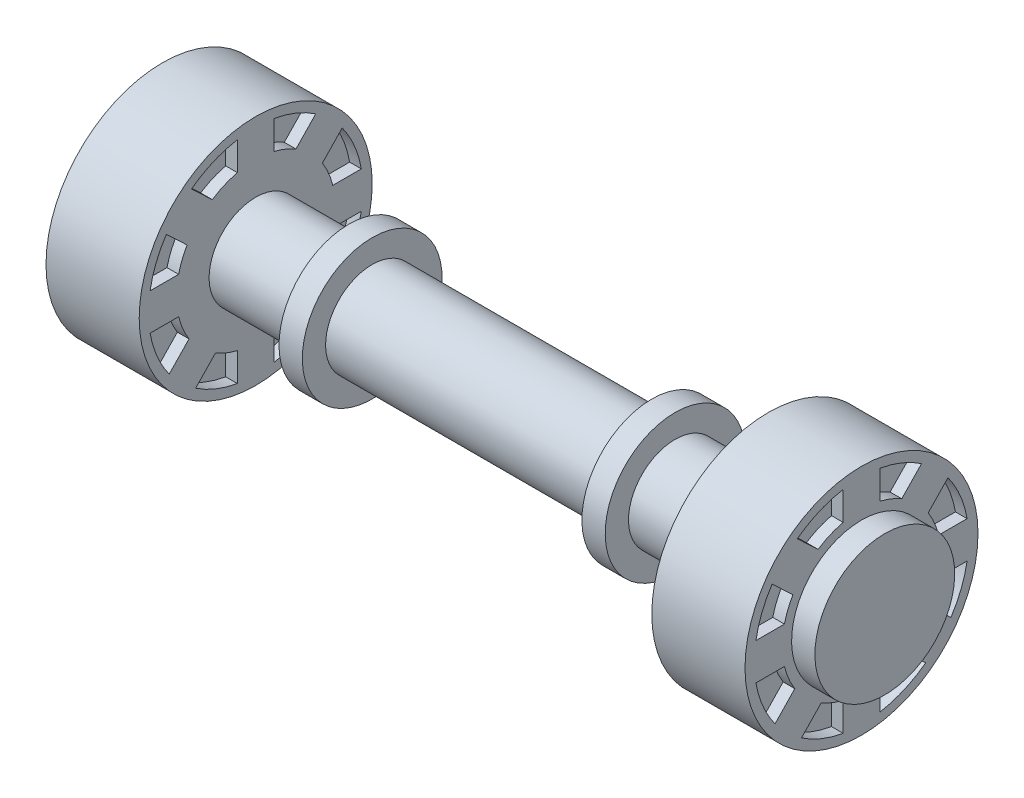
SolidWorks part; units mm, degrees
ref_plane "Front Plane" through (0, 0, 0) normal (0, 0, 1) x (1, 0, 0)
ref_plane "Top Plane" through (0, 0, 0) normal (0, 1, 0) x (1, 0, 0)
ref_plane "Right Plane" through (0, 0, 0) normal (1, 0, 0) x (0, 0, -1)
sketch "Sketch1" plane through (0, 0, 0) normal (0, 0, 1) x (1, 0, 0)
  line L0 (203.2, 0) -> (-203.2, 0)
  line L5 (-139.7, 25.4) -> (-139.7, 63.5)
  line L6 (-139.7, 63.5) -> (-190.5, 63.5)
  line L7 (-139.7, 25.4) -> (-88.9, 25.4)
  line L12 (-88.9, 25.4) -> (-88.9, 38.1)
  line L13 (-88.9, 38.1) -> (-76.2, 38.1)
  line L14 (-76.2, 38.1) -> (-76.2, 25.4)
  line L15 (-76.2, 25.4) -> (76.2, 25.4)
  line L16 (76.2, 25.4) -> (76.2, 38.1)
  line L17 (76.2, 38.1) -> (88.9, 38.1)
  line L18 (88.9, 38.1) -> (88.9, 25.4)
  line L19 (88.9, 25.4) -> (139.7, 25.4)
  line L20 (139.7, 25.4) -> (139.7, 63.5)
  line L21 (139.7, 63.5) -> (190.5, 63.5)
  line L22 (190.5, 63.5) -> (190.5, 38.1)
  line L23 (190.5, 38.1) -> (203.2, 38.1)
  line L24 (203.2, 38.1) -> (203.2, 0)
  line L25 (-190.5, 63.5) -> (-190.5, 38.1)
  line L26 (-190.5, 38.1) -> (-203.2, 38.1)
  line L27 (-203.2, 38.1) -> (-203.2, 0)
  point P4 (0, 0)
  point P7 (-165.1, 63.5)
  point P11 (165.1, 63.5)
  dimension "D1" = 406.4
  dimension "D2" = 50.8
  dimension "D3" = 50.8
  dimension "D4" = 12.7
  dimension "D5" = 12.7
  dimension "D6" = 63.5
  dimension "D7" = 38.1
  dimension "D8" = 25.4
  dimension "D9" = 152.4
  dimension "D10" = 12.7
  dimension "D11" = 12.7
  dimension "D12" = 76.2
  dimension "D13" = 330.2
revolve "Revolve1" add sketch "Sketch1" angle 360 about L0
sketch "Sketch2" plane through (190.5, 0, 0) normal (1, 0, 0) x (0, 0, -1)
  line L0 (0, 58.42) -> (0, 43.18) construction
  line L1 (58.42, 0) -> (43.18, 0) construction
  line L2 (42.4721, -40.1125) -> (31.3924, -29.6484) construction
  line L3 (40.5324, 42.0716) -> (29.9587, 31.0964) construction
  line L4 (-29.9587, -31.0964) -> (-40.5324, -42.0716) construction
  line L5 (0, -43.18) -> (0, -58.42) construction
  line L6 (-31.3924, 29.6484) -> (-42.4721, 40.1125) construction
  line L7 (-43.18, 0) -> (-58.42, 0) construction
  line L8 (-23.6728, 36.1125) -> (-34.979, 46.7906)
  line L9 (-42.0061, 10) -> (-57.5578, 10)
  line L10 (-36.3458, -23.3129) -> (-47.1358, -34.5126)
  line L11 (-10, -42.0061) -> (-10, -57.5578)
  line L12 (48.7115, -32.2504) -> (37.4052, -21.5722)
  line L13 (57.5578, 10) -> (42.0061, 10)
  line L14 (32.7326, 48.3888) -> (21.9427, 37.1891)
  line L15 (-37.4052, 21.5722) -> (-48.7115, 32.2504)
  line L16 (-42.0061, -10) -> (-57.5578, -10)
  line L17 (-21.9427, -37.1891) -> (-32.7326, -48.3888)
  line L18 (10, -42.0061) -> (10, -57.5578)
  line L19 (34.979, -46.7906) -> (23.6728, -36.1125)
  line L20 (57.5578, -10) -> (42.0061, -10)
  line L21 (47.1358, 34.5126) -> (36.3458, 23.3129)
  line L22 (-10, 57.5578) -> (-10, 42.0061)
  line L23 (10, 57.5578) -> (10, 42.0061)
  line L25 (47.734, 35.1335) -> (37.1603, 24.1583) construction
  line L26 (33.3308, 49.0097) -> (22.7572, 38.0345) construction
  line L27 (10, 58.42) -> (10, 43.18) construction
  line L28 (-10, 58.42) -> (-10, 43.18) construction
  line L29 (-24.5262, 36.9185) -> (-35.6059, 47.3827) construction
  line L30 (-38.2587, 22.3783) -> (-49.3383, 32.8424) construction
  line L31 (-43.18, -10) -> (-58.42, -10) construction
  line L32 (-43.18, 10) -> (-58.42, 10) construction
  line L33 (-37.1603, -24.1583) -> (-47.734, -35.1335) construction
  line L34 (-22.7572, -38.0345) -> (-33.3308, -49.0097) construction
  line L35 (-10, -43.18) -> (-10, -58.42) construction
  line L36 (10, -43.18) -> (10, -58.42) construction
  line L37 (35.6059, -47.3827) -> (24.5262, -36.9185) construction
  line L38 (49.3383, -32.8424) -> (38.2587, -22.3783) construction
  line L39 (58.42, 10) -> (43.18, 10) construction
  line L40 (58.42, -10) -> (43.18, -10) construction
  arc A0 (21.9427, 37.1891) -> (10, 42.0061) centre (0, 0) ccw
  arc A1 (32.7326, 48.3888) -> (10, 57.5578) centre (0, 0) ccw
  circle A2 centre (0, 0) radius 63.5 construction
  circle A3 centre (0, 0) radius 38.1 construction
  arc A4 (-10, 57.5578) -> (-34.979, 46.7906) centre (0, 0) ccw
  arc A5 (-10, 42.0061) -> (-23.6728, 36.1125) centre (0, 0) ccw
  arc A6 (-37.4052, 21.5722) -> (-42.0061, 10) centre (0, 0) ccw
  arc A7 (-48.7115, 32.2504) -> (-57.5578, 10) centre (0, 0) ccw
  arc A8 (-42.0061, -10) -> (-36.3458, -23.3129) centre (0, 0) ccw
  arc A9 (-57.5578, -10) -> (-47.1358, -34.5126) centre (0, 0) ccw
  arc A10 (-21.9427, -37.1891) -> (-10, -42.0061) centre (0, 0) ccw
  arc A11 (-32.7326, -48.3888) -> (-10, -57.5578) centre (0, 0) ccw
  arc A12 (10, -42.0061) -> (23.6728, -36.1125) centre (0, 0) ccw
  arc A13 (10, -57.5578) -> (34.979, -46.7906) centre (0, 0) ccw
  arc A14 (48.7115, -32.2504) -> (57.5578, -10) centre (0, 0) ccw
  arc A15 (37.4052, -21.5722) -> (42.0061, -10) centre (0, 0) ccw
  arc A16 (42.0061, 10) -> (36.3458, 23.3129) centre (0, 0) ccw
  arc A17 (57.5578, 10) -> (47.1358, 34.5126) centre (0, 0) ccw
  point P11 (0, 0)
  point P14 (0, 0)
  point P17 (0, 0)
  point P20 (0, 0)
  dimension "D1" = 5.08
  dimension "D2" = 5.08
  dimension "D3" = 10
  dimension "D4" = 10
  dimension "D5" = 10
  dimension "D6" = 10
extrude "Cut-Extrude1" cut sketch "Sketch2" against normal blind 6.35
sketch "Sketch3" plane through (-190.5, 0, 0) normal (-1, 0, 0) x (0, 0, 1)
  line L0 (57.5578, 10) -> (42.0061, 10) construction
  line L1 (37.4052, 21.5722) -> (48.7115, 32.2504) construction
  line L2 (47.1358, -34.5126) -> (36.3458, -23.3129) construction
  line L3 (42.0061, -10) -> (57.5578, -10) construction
  line L4 (10, -57.5578) -> (10, -42.0061) construction
  line L5 (21.9427, -37.1891) -> (32.7326, -48.3888) construction
  line L6 (-34.979, -46.7906) -> (-23.6728, -36.1125) construction
  line L7 (-10, -42.0061) -> (-10, -57.5578) construction
  line L8 (-57.5578, -10) -> (-42.0061, -10) construction
  line L9 (-37.4052, -21.5722) -> (-48.7115, -32.2504) construction
  line L10 (-47.1358, 34.5126) -> (-36.3458, 23.3129) construction
  line L11 (-42.0061, 10) -> (-57.5578, 10) construction
  line L12 (-10, 57.5578) -> (-10, 42.0061) construction
  line L13 (-21.9427, 37.1891) -> (-32.7326, 48.3888) construction
  line L14 (34.979, 46.7906) -> (23.6728, 36.1125) construction
  line L15 (10, 42.0061) -> (10, 57.5578) construction
  line L16 (57.5578, 10) -> (42.0061, 10)
  line L17 (37.4052, 21.5722) -> (48.7115, 32.2504)
  line L18 (47.1358, -34.5126) -> (36.3458, -23.3129)
  line L19 (42.0061, -10) -> (57.5578, -10)
  line L20 (10, -57.5578) -> (10, -42.0061)
  line L21 (21.9427, -37.1891) -> (32.7326, -48.3888)
  line L22 (-34.979, -46.7906) -> (-23.6728, -36.1125)
  line L23 (-10, -42.0061) -> (-10, -57.5578)
  line L24 (-57.5578, -10) -> (-42.0061, -10)
  line L25 (-37.4052, -21.5722) -> (-48.7115, -32.2504)
  line L26 (-47.1358, 34.5126) -> (-36.3458, 23.3129)
  line L27 (-42.0061, 10) -> (-57.5578, 10)
  line L28 (-10, 57.5578) -> (-10, 42.0061)
  line L29 (-21.9427, 37.1891) -> (-32.7326, 48.3888)
  line L30 (34.979, 46.7906) -> (23.6728, 36.1125)
  line L31 (10, 42.0061) -> (10, 57.5578)
  arc A0 (57.5578, 10) -> (48.7115, 32.2504) centre (0, 0) ccw construction
  arc A1 (42.0061, 10) -> (37.4052, 21.5722) centre (0, 0) ccw construction
  arc A2 (47.1358, -34.5126) -> (57.5578, -10) centre (0, 0) ccw construction
  arc A3 (36.3458, -23.3129) -> (42.0061, -10) centre (0, 0) ccw construction
  arc A4 (10, -57.5578) -> (32.7326, -48.3888) centre (0, 0) ccw construction
  arc A5 (10, -42.0061) -> (21.9427, -37.1891) centre (0, 0) ccw construction
  arc A6 (-34.979, -46.7906) -> (-10, -57.5578) centre (0, 0) ccw construction
  arc A7 (-23.6728, -36.1125) -> (-10, -42.0061) centre (0, 0) ccw construction
  arc A8 (-57.5578, -10) -> (-48.7115, -32.2504) centre (0, 0) ccw construction
  arc A9 (-42.0061, -10) -> (-37.4052, -21.5722) centre (0, 0) ccw construction
  arc A10 (-47.1358, 34.5126) -> (-57.5578, 10) centre (0, 0) ccw construction
  arc A11 (-36.3458, 23.3129) -> (-42.0061, 10) centre (0, 0) ccw construction
  arc A12 (-10, 57.5578) -> (-32.7326, 48.3888) centre (0, 0) ccw construction
  arc A13 (-10, 42.0061) -> (-21.9427, 37.1891) centre (0, 0) ccw construction
  arc A14 (34.979, 46.7906) -> (10, 57.5578) centre (0, 0) ccw construction
  arc A15 (23.6728, 36.1125) -> (10, 42.0061) centre (0, 0) ccw construction
  arc A16 (57.5578, 10) -> (48.7115, 32.2504) centre (0, 0) ccw
  arc A17 (42.0061, 10) -> (37.4052, 21.5722) centre (0, 0) ccw
  arc A18 (47.1358, -34.5126) -> (57.5578, -10) centre (0, 0) ccw
  arc A19 (36.3458, -23.3129) -> (42.0061, -10) centre (0, 0) ccw
  arc A20 (10, -57.5578) -> (32.7326, -48.3888) centre (0, 0) ccw
  arc A21 (10, -42.0061) -> (21.9427, -37.1891) centre (0, 0) ccw
  arc A22 (-34.979, -46.7906) -> (-10, -57.5578) centre (0, 0) ccw
  arc A23 (-23.6728, -36.1125) -> (-10, -42.0061) centre (0, 0) ccw
  arc A24 (-57.5578, -10) -> (-48.7115, -32.2504) centre (0, 0) ccw
  arc A25 (-42.0061, -10) -> (-37.4052, -21.5722) centre (0, 0) ccw
  arc A26 (-47.1358, 34.5126) -> (-57.5578, 10) centre (0, 0) ccw
  arc A27 (-36.3458, 23.3129) -> (-42.0061, 10) centre (0, 0) ccw
  arc A28 (-10, 57.5578) -> (-32.7326, 48.3888) centre (0, 0) ccw
  arc A29 (-10, 42.0061) -> (-21.9427, 37.1891) centre (0, 0) ccw
  arc A30 (34.979, 46.7906) -> (10, 57.5578) centre (0, 0) ccw
  arc A31 (23.6728, 36.1125) -> (10, 42.0061) centre (0, 0) ccw
extrude "Cut-Extrude2" cut sketch "Sketch3" against normal blind 6.35
sketch "Sketch4" plane through (0, 0, 0) normal (0, 0, 1) x (1, 0, 0)
  line L0 (203.2, -38.1) -> (203.2, 38.1) construction
  line L1 (203.2, 38.1) -> (190.5, 38.1) construction
  line L2 (190.5, -38.1) -> (190.5, 38.1) construction
  line L3 (139.7, 25.4) -> (139.7, -25.4) construction
  line L4 (139.7, 25.4) -> (88.9, 25.4) construction
  line L5 (88.9, -38.1) -> (88.9, 38.1) construction
  line L6 (88.9, 38.1) -> (76.2, 38.1) construction
  line L7 (76.2, 38.1) -> (76.2, -38.1) construction
  line L8 (76.2, 25.4) -> (-76.2, 25.4) construction
  line L9 (-76.2, -38.1) -> (-76.2, 38.1) construction
  line L10 (-76.2, 38.1) -> (-88.9, 38.1) construction
  line L11 (-88.9, 38.1) -> (-88.9, -38.1) construction
  line L12 (-88.9, 25.4) -> (-139.7, 25.4) construction
  line L13 (-139.7, -25.4) -> (-139.7, 25.4) construction
  line L14 (-190.5, 38.1) -> (-190.5, -38.1) construction
  line L15 (-190.5, 38.1) -> (-203.2, 38.1) construction
  line L16 (-203.2, 38.1) -> (-203.2, -38.1) construction
  line L17 (203.2, 0) -> (203.2, 38.1) construction
  line L18 (203.2, 38.1) -> (190.5, 38.1) construction
  line L19 (190.5, 0) -> (190.5, 38.1) construction
  line L20 (139.7, 25.4) -> (139.7, 0) construction
  line L21 (139.7, 25.4) -> (88.9, 25.4) construction
  line L22 (88.9, 25.4) -> (88.9, 38.1) construction
  line L23 (88.9, 38.1) -> (76.2, 38.1) construction
  line L24 (76.2, 38.1) -> (76.2, 25.4) construction
  line L25 (76.2, 25.4) -> (-76.2, 25.4) construction
  line L26 (-76.2, 25.4) -> (-76.2, 38.1) construction
  line L27 (-76.2, 38.1) -> (-88.9, 38.1) construction
  line L28 (-88.9, 38.1) -> (-88.9, 25.4) construction
  line L29 (-88.9, 25.4) -> (-139.7, 25.4) construction
  line L30 (-139.7, 0) -> (-139.7, 25.4) construction
  line L31 (-190.5, 38.1) -> (-190.5, 0) construction
  line L32 (-190.5, 38.1) -> (-203.2, 38.1) construction
  line L33 (-203.2, 38.1) -> (-203.2, 0) construction
  line L34 (-203.2, 0) -> (-190.5, 0) construction
  line L35 (190.5, 0) -> (203.2, 0) construction
  line L36 (-139.7, 0) -> (139.7, 0) construction
  line L37 (198.12, 0) -> (198.12, 33.02)
  line L38 (198.12, 33.02) -> (195.58, 33.02)
  line L39 (195.58, 0) -> (195.58, 33.02)
  line L41 (134.62, 20.32) -> (134.62, 0)
  line L43 (-134.62, 0) -> (-134.62, 20.32)
  line L44 (-83.82, 20.32) -> (-134.62, 20.32)
  line L45 (-83.82, 33.02) -> (-83.82, 20.32)
  line L46 (-81.28, 33.02) -> (-83.82, 33.02)
  line L47 (-81.28, 20.32) -> (-81.28, 33.02)
  line L48 (81.28, 20.32) -> (-81.28, 20.32)
  line L49 (81.28, 33.02) -> (81.28, 20.32)
  line L50 (83.82, 33.02) -> (81.28, 33.02)
  line L51 (83.82, 20.32) -> (83.82, 33.02)
  line L52 (134.62, 20.32) -> (83.82, 20.32)
  line L53 (-195.58, 33.02) -> (-195.58, 0)
  line L55 (-198.12, 33.02) -> (-198.12, 0)
  line L56 (-195.58, 33.02) -> (-198.12, 33.02)
  line L57 (-134.62, 5.08) -> (134.62, 5.08) construction
  line L58 (195.58, 5.08) -> (198.12, 5.08) construction
  line L59 (-198.12, 5.08) -> (-195.58, 5.08) construction
  line L60 (-198.12, 33.02) -> (-198.12, 5.08) construction
  line L61 (-195.58, 33.02) -> (-195.58, 5.08) construction
  line L62 (-134.62, 5.08) -> (-134.62, 20.32) construction
  line L63 (134.62, 20.32) -> (134.62, 5.08) construction
  line L64 (198.12, 5.08) -> (198.12, 33.02) construction
  line L65 (195.58, 5.08) -> (195.58, 33.02) construction
  line L66 (-198.12, 0) -> (-195.58, 0)
  line L67 (134.62, 0) -> (-134.62, 0)
  line L68 (198.12, 0) -> (195.58, 0)
  dimension "D1" = 5.08
revolve "Cut-Revolve1" cut sketch "Sketch4" angle 360 about L36
sketch "Sketch5" plane through (-139.7, 0, 0) normal (1, 0, 0) x (0, 0, -1)
  line L0 (57.5578, 10) -> (42.0061, 10) construction
  line L1 (36.3458, 23.3129) -> (47.1358, 34.5126) construction
  line L2 (48.7115, -32.2504) -> (37.4052, -21.5722) construction
  line L3 (42.0061, -10) -> (57.5578, -10) construction
  line L4 (10, -57.5578) -> (10, -42.0061) construction
  line L5 (23.6728, -36.1125) -> (34.979, -46.7906) construction
  line L6 (-32.7326, -48.3888) -> (-21.9427, -37.1891) construction
  line L7 (-10, -42.0061) -> (-10, -57.5578) construction
  line L8 (-57.5578, -10) -> (-42.0061, -10) construction
  line L9 (-36.3458, -23.3129) -> (-47.1358, -34.5126) construction
  line L10 (-48.7115, 32.2504) -> (-37.4052, 21.5722) construction
  line L11 (-42.0061, 10) -> (-57.5578, 10) construction
  line L12 (-10, 57.5578) -> (-10, 42.0061) construction
  line L13 (-23.6728, 36.1125) -> (-34.979, 46.7906) construction
  line L14 (32.7326, 48.3888) -> (21.9427, 37.1891) construction
  line L15 (10, 42.0061) -> (10, 57.5578) construction
  line L16 (57.5578, 10) -> (42.0061, 10)
  line L17 (36.3458, 23.3129) -> (47.1358, 34.5126)
  line L18 (48.7115, -32.2504) -> (37.4052, -21.5722)
  line L19 (42.0061, -10) -> (57.5578, -10)
  line L20 (10, -57.5578) -> (10, -42.0061)
  line L21 (23.6728, -36.1125) -> (34.979, -46.7906)
  line L22 (-32.7326, -48.3888) -> (-21.9427, -37.1891)
  line L23 (-10, -42.0061) -> (-10, -57.5578)
  line L24 (-57.5578, -10) -> (-42.0061, -10)
  line L25 (-36.3458, -23.3129) -> (-47.1358, -34.5126)
  line L26 (-48.7115, 32.2504) -> (-37.4052, 21.5722)
  line L27 (-42.0061, 10) -> (-57.5578, 10)
  line L28 (-10, 57.5578) -> (-10, 42.0061)
  line L29 (-23.6728, 36.1125) -> (-34.979, 46.7906)
  line L30 (32.7326, 48.3888) -> (21.9427, 37.1891)
  line L31 (10, 42.0061) -> (10, 57.5578)
  arc A0 (57.5578, 10) -> (47.1358, 34.5126) centre (0, 0) ccw construction
  arc A1 (42.0061, 10) -> (36.3458, 23.3129) centre (0, 0) ccw construction
  arc A2 (48.7115, -32.2504) -> (57.5578, -10) centre (0, 0) ccw construction
  arc A3 (37.4052, -21.5722) -> (42.0061, -10) centre (0, 0) ccw construction
  arc A4 (10, -57.5578) -> (34.979, -46.7906) centre (0, 0) ccw construction
  arc A5 (10, -42.0061) -> (23.6728, -36.1125) centre (0, 0) ccw construction
  arc A6 (-32.7326, -48.3888) -> (-10, -57.5578) centre (0, 0) ccw construction
  arc A7 (-21.9427, -37.1891) -> (-10, -42.0061) centre (0, 0) ccw construction
  arc A8 (-57.5578, -10) -> (-47.1358, -34.5126) centre (0, 0) ccw construction
  arc A9 (-42.0061, -10) -> (-36.3458, -23.3129) centre (0, 0) ccw construction
  arc A10 (-48.7115, 32.2504) -> (-57.5578, 10) centre (0, 0) ccw construction
  arc A11 (-37.4052, 21.5722) -> (-42.0061, 10) centre (0, 0) ccw construction
  arc A12 (-10, 57.5578) -> (-34.979, 46.7906) centre (0, 0) ccw construction
  arc A13 (-10, 42.0061) -> (-23.6728, 36.1125) centre (0, 0) ccw construction
  arc A14 (32.7326, 48.3888) -> (10, 57.5578) centre (0, 0) ccw construction
  arc A15 (21.9427, 37.1891) -> (10, 42.0061) centre (0, 0) ccw construction
  arc A16 (57.5578, 10) -> (47.1358, 34.5126) centre (0, 0) ccw
  arc A17 (42.0061, 10) -> (36.3458, 23.3129) centre (0, 0) ccw
  arc A18 (48.7115, -32.2504) -> (57.5578, -10) centre (0, 0) ccw
  arc A19 (37.4052, -21.5722) -> (42.0061, -10) centre (0, 0) ccw
  arc A20 (10, -57.5578) -> (34.979, -46.7906) centre (0, 0) ccw
  arc A21 (10, -42.0061) -> (23.6728, -36.1125) centre (0, 0) ccw
  arc A22 (-32.7326, -48.3888) -> (-10, -57.5578) centre (0, 0) ccw
  arc A23 (-21.9427, -37.1891) -> (-10, -42.0061) centre (0, 0) ccw
  arc A24 (-57.5578, -10) -> (-47.1358, -34.5126) centre (0, 0) ccw
  arc A25 (-42.0061, -10) -> (-36.3458, -23.3129) centre (0, 0) ccw
  arc A26 (-48.7115, 32.2504) -> (-57.5578, 10) centre (0, 0) ccw
  arc A27 (-37.4052, 21.5722) -> (-42.0061, 10) centre (0, 0) ccw
  arc A28 (-10, 57.5578) -> (-34.979, 46.7906) centre (0, 0) ccw
  arc A29 (-10, 42.0061) -> (-23.6728, 36.1125) centre (0, 0) ccw
  arc A30 (32.7326, 48.3888) -> (10, 57.5578) centre (0, 0) ccw
  arc A31 (21.9427, 37.1891) -> (10, 42.0061) centre (0, 0) ccw
extrude "Cut-Extrude3" cut sketch "Sketch5" against normal blind 6.35
sketch "Sketch6" plane through (139.7, 0, 0) normal (-1, 0, 0) x (0, 0, 1)
  line L0 (48.7115, 32.2504) -> (37.4052, 21.5722) construction
  line L1 (42.0061, 10) -> (57.5578, 10) construction
  line L2 (57.5578, -10) -> (42.0061, -10) construction
  line L3 (36.3458, -23.3129) -> (47.1358, -34.5126) construction
  line L4 (32.7326, -48.3888) -> (21.9427, -37.1891) construction
  line L5 (10, -42.0061) -> (10, -57.5578) construction
  line L6 (-10, -57.5578) -> (-10, -42.0061) construction
  line L7 (-23.6728, -36.1125) -> (-34.979, -46.7906) construction
  line L8 (-48.7115, -32.2504) -> (-37.4052, -21.5722) construction
  line L9 (-42.0061, -10) -> (-57.5578, -10) construction
  line L10 (-57.5578, 10) -> (-42.0061, 10) construction
  line L11 (-36.3458, 23.3129) -> (-47.1358, 34.5126) construction
  line L12 (-32.7326, 48.3888) -> (-21.9427, 37.1891) construction
  line L13 (-10, 42.0061) -> (-10, 57.5578) construction
  line L14 (10, 57.5578) -> (10, 42.0061) construction
  line L15 (23.6728, 36.1125) -> (34.979, 46.7906) construction
  line L16 (48.7115, 32.2504) -> (37.4052, 21.5722)
  line L17 (42.0061, 10) -> (57.5578, 10)
  line L18 (57.5578, -10) -> (42.0061, -10)
  line L19 (36.3458, -23.3129) -> (47.1358, -34.5126)
  line L20 (32.7326, -48.3888) -> (21.9427, -37.1891)
  line L21 (10, -42.0061) -> (10, -57.5578)
  line L22 (-10, -57.5578) -> (-10, -42.0061)
  line L23 (-23.6728, -36.1125) -> (-34.979, -46.7906)
  line L24 (-48.7115, -32.2504) -> (-37.4052, -21.5722)
  line L25 (-42.0061, -10) -> (-57.5578, -10)
  line L26 (-57.5578, 10) -> (-42.0061, 10)
  line L27 (-36.3458, 23.3129) -> (-47.1358, 34.5126)
  line L28 (-32.7326, 48.3888) -> (-21.9427, 37.1891)
  line L29 (-10, 42.0061) -> (-10, 57.5578)
  line L30 (10, 57.5578) -> (10, 42.0061)
  line L31 (23.6728, 36.1125) -> (34.979, 46.7906)
  arc A0 (57.5578, 10) -> (48.7115, 32.2504) centre (0, 0) ccw construction
  arc A1 (42.0061, 10) -> (37.4052, 21.5722) centre (0, 0) ccw construction
  arc A2 (47.1358, -34.5126) -> (57.5578, -10) centre (0, 0) ccw construction
  arc A3 (36.3458, -23.3129) -> (42.0061, -10) centre (0, 0) ccw construction
  arc A4 (10, -57.5578) -> (32.7326, -48.3888) centre (0, 0) ccw construction
  arc A5 (10, -42.0061) -> (21.9427, -37.1891) centre (0, 0) ccw construction
  arc A6 (-34.979, -46.7906) -> (-10, -57.5578) centre (0, 0) ccw construction
  arc A7 (-23.6728, -36.1125) -> (-10, -42.0061) centre (0, 0) ccw construction
  arc A8 (-57.5578, -10) -> (-48.7115, -32.2504) centre (0, 0) ccw construction
  arc A9 (-42.0061, -10) -> (-37.4052, -21.5722) centre (0, 0) ccw construction
  arc A10 (-47.1358, 34.5126) -> (-57.5578, 10) centre (0, 0) ccw construction
  arc A11 (-36.3458, 23.3129) -> (-42.0061, 10) centre (0, 0) ccw construction
  arc A12 (-10, 57.5578) -> (-32.7326, 48.3888) centre (0, 0) ccw construction
  arc A13 (-10, 42.0061) -> (-21.9427, 37.1891) centre (0, 0) ccw construction
  arc A14 (34.979, 46.7906) -> (10, 57.5578) centre (0, 0) ccw construction
  arc A15 (23.6728, 36.1125) -> (10, 42.0061) centre (0, 0) ccw construction
  arc A16 (57.5578, 10) -> (48.7115, 32.2504) centre (0, 0) ccw
  arc A17 (42.0061, 10) -> (37.4052, 21.5722) centre (0, 0) ccw
  arc A18 (47.1358, -34.5126) -> (57.5578, -10) centre (0, 0) ccw
  arc A19 (36.3458, -23.3129) -> (42.0061, -10) centre (0, 0) ccw
  arc A20 (10, -57.5578) -> (32.7326, -48.3888) centre (0, 0) ccw
  arc A21 (10, -42.0061) -> (21.9427, -37.1891) centre (0, 0) ccw
  arc A22 (-34.979, -46.7906) -> (-10, -57.5578) centre (0, 0) ccw
  arc A23 (-23.6728, -36.1125) -> (-10, -42.0061) centre (0, 0) ccw
  arc A24 (-57.5578, -10) -> (-48.7115, -32.2504) centre (0, 0) ccw
  arc A25 (-42.0061, -10) -> (-37.4052, -21.5722) centre (0, 0) ccw
  arc A26 (-47.1358, 34.5126) -> (-57.5578, 10) centre (0, 0) ccw
  arc A27 (-36.3458, 23.3129) -> (-42.0061, 10) centre (0, 0) ccw
  arc A28 (-10, 57.5578) -> (-32.7326, 48.3888) centre (0, 0) ccw
  arc A29 (-10, 42.0061) -> (-21.9427, 37.1891) centre (0, 0) ccw
  arc A30 (34.979, 46.7906) -> (10, 57.5578) centre (0, 0) ccw
  arc A31 (23.6728, 36.1125) -> (10, 42.0061) centre (0, 0) ccw
extrude "Cut-Extrude4" cut sketch "Sketch6" against normal blind 6.35
